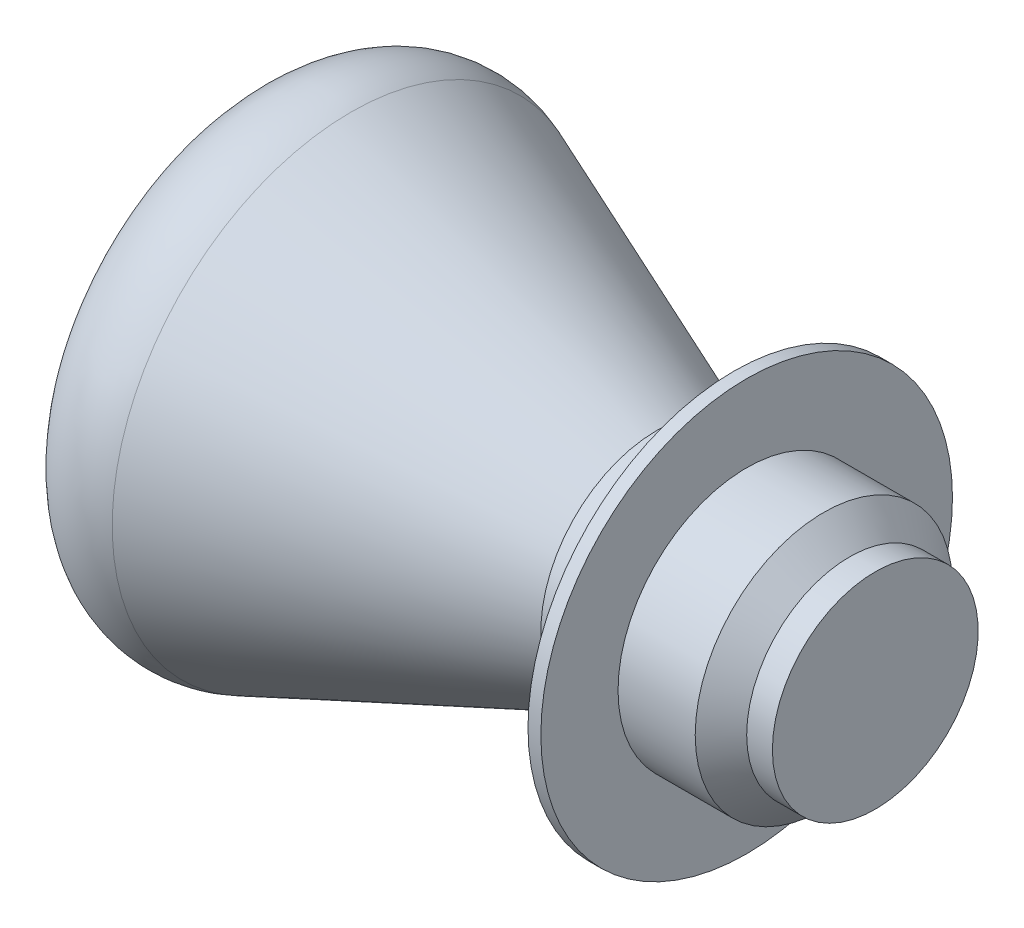
SolidWorks part; units mm, degrees
ref_plane "Front Plane" through (0, 0, 0) normal (0, 0, 1) x (1, 0, 0)
ref_plane "Top Plane" through (0, 0, 0) normal (0, 1, 0) x (1, 0, 0)
ref_plane "Right Plane" through (0, 0, 0) normal (1, 0, 0) x (0, 0, -1)
sketch "Sketch1" plane through (0, 0, 0) normal (0, 0, 1) x (1, 0, 0)
  line L0 (0, 0) -> (5.5, 0)
  line L1 (5.5, 0) -> (5.5, 4)
  line L2 (5.5, 4) -> (4.5, 4)
  line L8 (0, 5) -> (-2, 5)
  line L9 (-2, 5) -> (-2, 4.5)
  line L10 (-2, 4.5) -> (0, 4.5)
  line L11 (0, 4.5) -> (0, 0)
  line L12 (0, 5) -> (0, 8)
  line L13 (0, 8) -> (0.5, 8)
  line L14 (0.5, 8) -> (0.5, 5)
  line L15 (0.5, 5) -> (3.5, 5)
  line L16 (4.5, 4) -> (3.5, 5)
  dimension "D1" = 5.5
  dimension "D2" = 5
  dimension "D3" = 1
  dimension "D4" = 1
  dimension "D5" = 1
  dimension "D6" = 3
  dimension "D7" = 0.5
  dimension "D8" = 3
  dimension "D9" = 2
revolve "Revolve1" add sketch "Sketch1" angle 360 about L0
sketch "Sketch2" plane through (0, 0, 0) normal (0, 0, 1) x (1, 0, 0)
  line L0 (0, 0) -> (-10.8351, 0) construction
  line L1 (0, 0) -> (0, 4.5)
  line L2 (0, 4.5) -> (-3, 4.5)
  line L3 (-3, 4.5) -> (-14.8796, 9.2829)
  line L4 (-19.8584, 0) -> (0, 0)
  arc A0 (-18.8972, 7.2788) -> (-19.8584, 0) centre (8.1816, 0) ccw
  arc A1 (-14.8796, 9.2829) -> (-18.8972, 7.2788) centre (-16, 6.5) ccw
  point P11 (0, 0)
  dimension "D1" = 3
  dimension "D4" = 28.04
  dimension "D2" = 16
  dimension "D3" = 2
  dimension "D5" = 3
revolve "Revolve2" add sketch "Sketch2" angle 360 about L4
